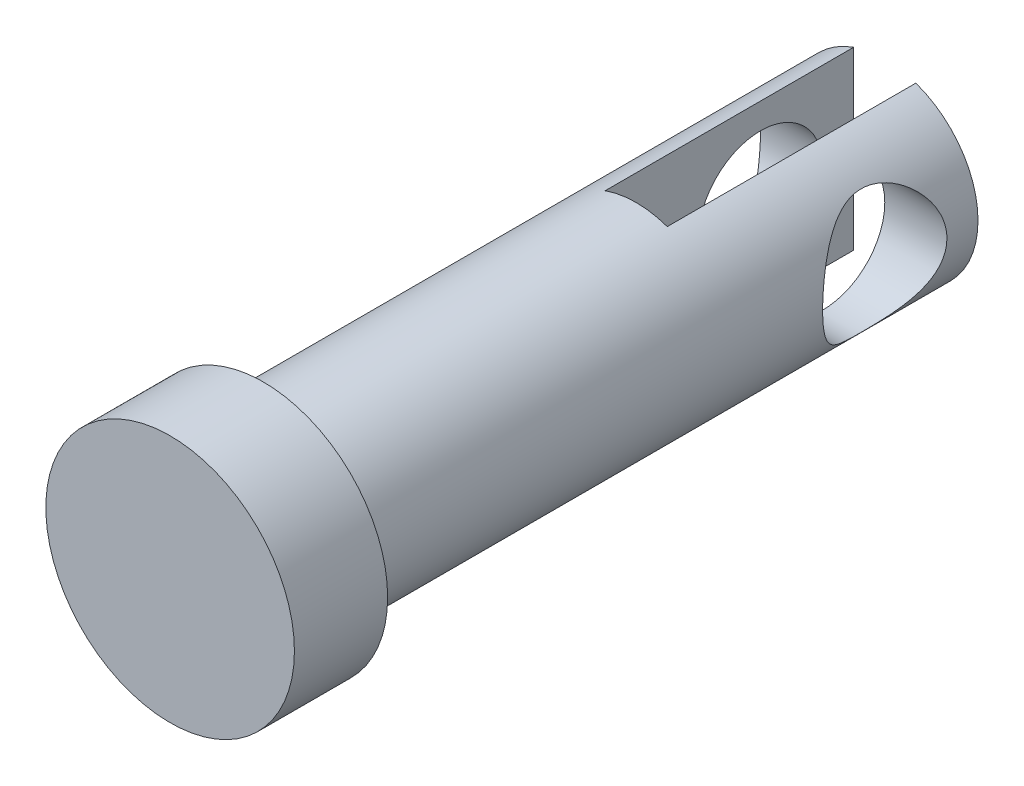
SolidWorks part; units mm, degrees
ref_plane "前视基准面" through (0, 0, 0) normal (0, 0, 1) x (1, 0, 0)
ref_plane "上视基准面" through (0, 0, 0) normal (0, 1, 0) x (1, 0, 0)
ref_plane "右视基准面" through (0, 0, 0) normal (1, 0, 0) x (0, 0, -1)
sketch "草图1" plane through (0, 0, 0) normal (0, 0, 1) x (1, 0, 0)
  circle A0 centre (0, 0) radius 3
  dimension "D1" = 6
extrude "凸台-拉伸1" add sketch "草图1" along normal blind 20
sketch "草图2" plane through (0, 0, 20) normal (0, 0, 1) x (1, 0, 0)
  circle A0 centre (0, 0) radius 4
  dimension "D1" = 8
extrude "凸台-拉伸2" add sketch "草图2" along normal blind 3
sketch "草图4" plane through (0, 0, 0) normal (0, 0, -1) x (-1, 0, 0)
  line L1 (-1, 3.4176) -> (1, 3.4176)
  line L2 (-1, 3.4176) -> (-1, -3.4176)
  line L3 (-1, -3.4176) -> (1, -3.4176)
  line L4 (1, 3.4176) -> (1, -3.4176)
  line L5 (0, -3.4176) -> (0, 3.4176) construction
  line L6 (-1, 0) -> (1, 0) construction
  point P0 (0, 0)
  dimension "D1" = 2
extrude "切除-拉伸1" cut sketch "草图4" against normal blind 8
sketch "草图5" plane through (0, 0, 0) normal (1, 0, 0) x (0, 0, -1)
  circle A0 centre (-3, 0) radius 2
  dimension "D1" = 4
  dimension "D2" = 3
extrude "切除-拉伸2" cut sketch "草图5" against normal mid plane 8
